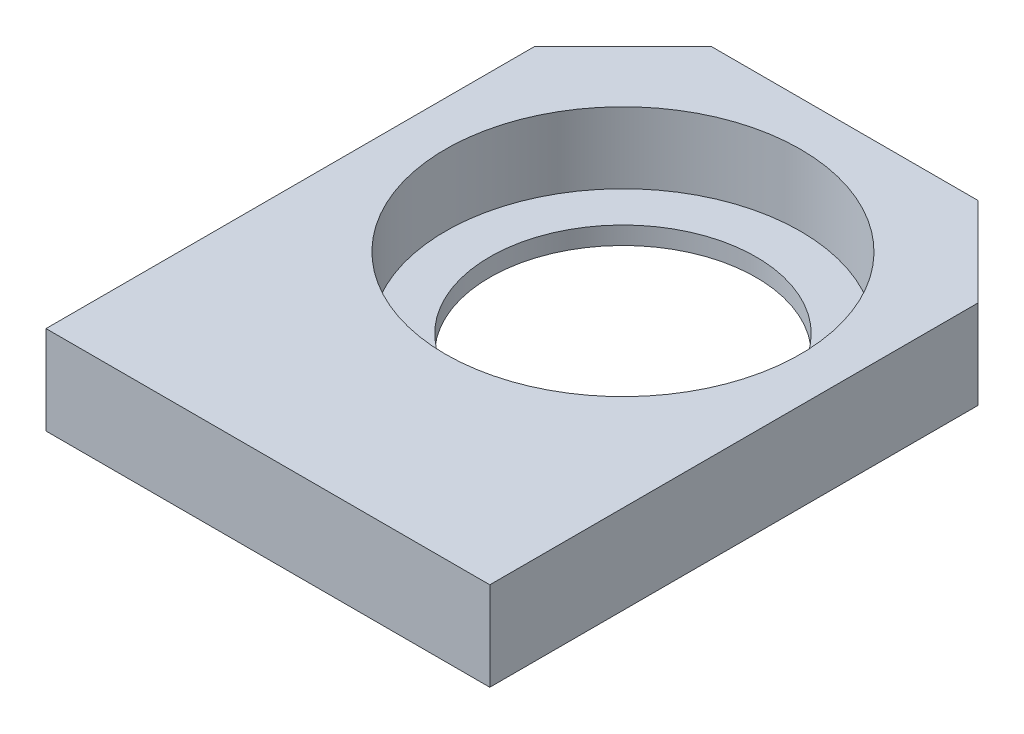
SolidWorks part; units mm, degrees
material "Acrylic (Medium-high impact)"
ref_plane "Front Plane" through (0, 0, 0) normal (0, 0, 1) x (1, 0, 0)
ref_plane "Top Plane" through (0, 0, 0) normal (0, 1, 0) x (1, 0, 0)
ref_plane "Right Plane" through (0, 0, 0) normal (1, 0, 0) x (0, 0, -1)
sketch "Sketch1" plane through (0, 0, 0) normal (1, 0, 0) x (0, 0, -1)
  line L1 (-20.6375, 6.35) -> (20.6375, 6.35)
  line L2 (-20.6375, 6.35) -> (-20.6375, 0)
  line L3 (-20.6375, 0) -> (20.6375, 0)
  line L4 (20.6375, 6.35) -> (20.6375, 0)
  line L5 (-20.6375, 6.35) -> (20.6375, 0) construction
  line L6 (-20.6375, 0) -> (20.6375, 6.35) construction
  point P0 (0, 3.175)
  dimension "D1" = 6.35
  dimension "D2" = 41.275
extrude "Boss-Extrude1" add sketch "Sketch1" along normal mid plane 31.75
sketch "Sketch2" plane through (15.875, 0, 0) normal (1, 0, 0) x (0, 0, -1)
  line L0 (-7.62, 4.7625) -> (7.62, 4.7625) construction
  line L1 (-20.6375, 0) -> (20.6375, 0) construction
  circle A0 centre (-7.62, 4.7625) radius 2.3813
  circle A1 centre (7.62, 4.7625) radius 2.3813
  point P6 (0, 4.7625)
  dimension "D2" = 4.7625
  dimension "D1" = 15.24
  dimension "D3" = 4.7625
extrude "Cut-Extrude1" [suppressed] cut sketch "Sketch2" against normal through all
sketch "Sketch4" plane through (0, 6.35, 0) normal (0, 1, 0) x (1, 0, 0)
  line L1 (15.875, -20.6375) -> (-15.875, -20.6375) construction
  circle A0 centre (0, 4.7625) radius 12.7
  dimension "D1" = 25.4
  dimension "D2" = 25.4
extrude "Cut-Extrude4" cut sketch "Sketch4" against normal blind 5.08
sketch "Sketch5" plane through (0, 1.27, 0) normal (0, 1, 0) x (1, 0, 0)
  circle A0 centre (0, 4.7625) radius 9.525
  point P3 (0, 3.175)
  dimension "D1" = 19.05
extrude "Cut-Extrude5" cut sketch "Sketch5" against normal blind 6.35
chamfer "Chamfer1" distance 6.35 angle 45 2 edges at (15.875, 3.175, -20.6375) (-15.875, 3.175, -20.6375)
